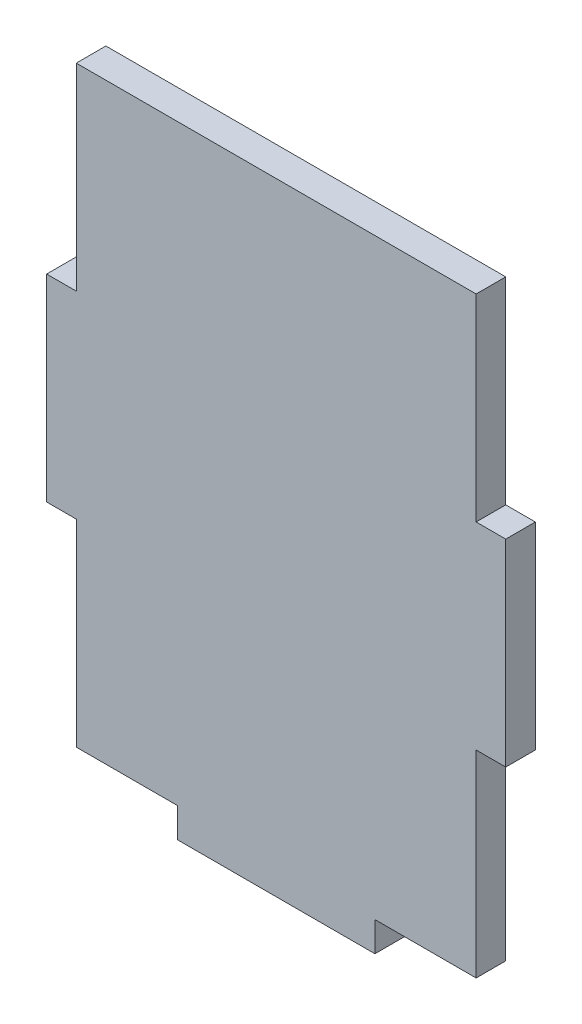
SolidWorks part; units mm, degrees
material "雪松树"
ref_plane "前视基准面" through (0, 0, 0) normal (0, 0, 1) x (1, 0, 0)
ref_plane "上视基准面" through (0, 0, 0) normal (0, 1, 0) x (1, 0, 0)
ref_plane "右视基准面" through (0, 0, 0) normal (1, 0, 0) x (0, 0, -1)
other "Configuration Table"
sketch "草图1" plane through (0, 0, 0) normal (0, 0, 1) x (1, 0, 0)
  line L1 (0, 0) -> (40.5, 0)
  line L2 (0, 0) -> (0, 60)
  line L3 (0, 60) -> (40.5, 60)
  line L4 (40.5, 0) -> (40.5, 60)
  line L5 (10.25, 0) -> (30.25, 0)
  line L6 (10.25, 0) -> (10.25, -3)
  line L7 (10.25, -3) -> (30.25, -3)
  line L8 (30.25, 0) -> (30.25, -3)
  line L9 (0, 40) -> (-3, 40)
  line L10 (0, 40) -> (0, 20)
  line L11 (0, 20) -> (-3, 20)
  line L12 (-3, 40) -> (-3, 20)
  line L13 (40.5, 40) -> (43.5, 40)
  line L14 (40.5, 40) -> (40.5, 20)
  line L15 (40.5, 20) -> (43.5, 20)
  line L16 (43.5, 40) -> (43.5, 20)
  dimension "D1" = 60
  dimension "D2" = 40.5
  dimension "D3" = 3
  dimension "D4" = 20
  dimension "D5" = 10.25
  dimension "D6" = 20
  dimension "D7" = 3
  dimension "D8" = 20
  dimension "D9" = 3
  dimension "D10" = 20
  dimension "D11" = 20
extrude "凸台-拉伸1" add sketch "草图1" along normal blind 3 contours L1 L4 L3 L2 | L16 L13 L4 L15 | L8 L1 L6 L7 | L12 L11 L10 L9
